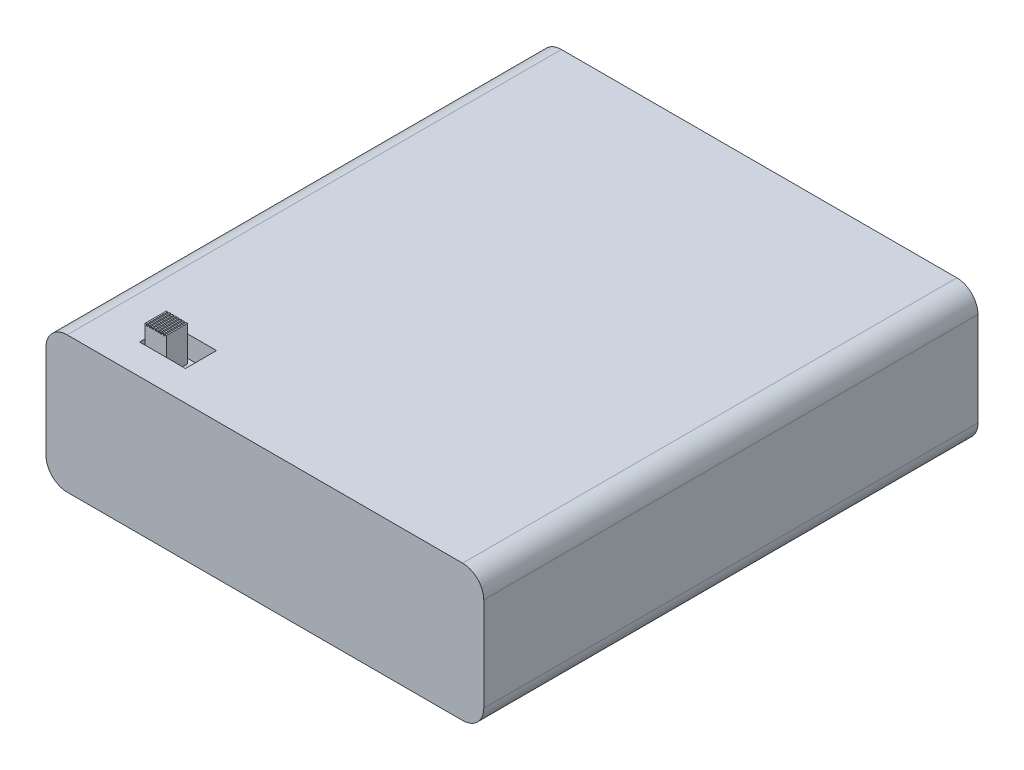
SolidWorks part; units mm, degrees
ref_plane "Front" through (0, 0, 0) normal (0, 0, 1) x (1, 0, 0)
ref_plane "Top" through (0, 0, 0) normal (0, 1, 0) x (1, 0, 0)
ref_plane "Right" through (0, 0, 0) normal (1, 0, 0) x (0, 0, -1)
sketch "Sketch1" plane through (0, 0, 0) normal (0, 0, 1) x (1, 0, 0)
  line L1 (-28, 9.65) -> (28, 9.65)
  line L2 (-31, 6.65) -> (-31, -6.65)
  line L3 (-28, -9.65) -> (28, -9.65)
  line L4 (31, 6.65) -> (31, -6.65)
  line L5 (-31, 9.65) -> (31, -9.65) construction
  line L6 (-31, -9.65) -> (31, 9.65) construction
  arc A0 (28, 9.65) -> (31, 6.65) centre (28, 6.65) cw
  arc A1 (28, -9.65) -> (31, -6.65) centre (28, -6.65) ccw
  arc A2 (-31, -6.65) -> (-28, -9.65) centre (-28, -6.65) ccw
  arc A3 (-28, 9.65) -> (-31, 6.65) centre (-28, 6.65) ccw
  point P0 (0, 0)
  dimension "D3" = 3
  dimension "D1" = 62
  dimension "D2" = 19.3
extrude "Boss-Extrude1" add sketch "Sketch1" along normal mid plane 70
sketch "Sketch2" plane through (0, 9.65, 0) normal (0, 1, 0) x (1, 0, 0)
  line L0 (-31, -35) -> (-31, 35) construction
  line L1 (-22, -26.35) -> (-15.5, -26.35)
  line L2 (-22, -26.35) -> (-22, -30.75)
  line L3 (-22, -30.75) -> (-15.5, -30.75)
  line L4 (-15.5, -26.35) -> (-15.5, -30.75)
  line L5 (28, -35) -> (-28, -35) construction
  dimension "D1" = 6.5
  dimension "D2" = 4.4
  dimension "D3" = 9
  dimension "D4" = 4.25
extrude "Cut-Extrude1" cut sketch "Sketch2" against normal blind 3
sketch "Sketch3" plane through (0, 6.65, 0) normal (0, 1, 0) x (1, 0, 0)
  line L0 (-22, -28.55) -> (-15.5, -28.55) construction
  line L1 (-21.9, -27.05) -> (-18.9, -27.05)
  line L2 (-21.9, -27.05) -> (-21.9, -30.05)
  line L3 (-21.9, -30.05) -> (-18.9, -30.05)
  line L4 (-18.9, -27.05) -> (-18.9, -30.05)
  line L5 (-22, -26.35) -> (-22, -30.75) construction
  line L6 (-15.5, -30.75) -> (-15.5, -26.35) construction
  line L7 (-22, -26.35) -> (-22, -30.75) construction
  point P10 (-21.9, -28.55)
  dimension "D1" = 3
  dimension "D2" = 0.1
extrude "Boss-Extrude2" add sketch "Sketch3" along normal blind 5
sketch "Sketch4" plane through (0, 0, 30.05) normal (0, 0, 1) x (1, 0, 0)
  line L0 (-21.9, 11.65) -> (-18.9, 11.65) construction
  line L1 (-21.7023, 11.65) -> (-21.5023, 11.65)
  line L2 (-21.7023, 11.65) -> (-21.7023, 11.45)
  line L3 (-21.7023, 11.45) -> (-21.5023, 11.45)
  line L4 (-21.5023, 11.65) -> (-21.5023, 11.45)
  line L5 (-21.9, 11.65) -> (-21.9, 6.65) construction
  line L14 (-21.3023, 11.65) -> (-21.3023, 11.45)
  line L15 (-21.3023, 11.65) -> (-21.1023, 11.65)
  line L16 (-21.1023, 11.65) -> (-21.1023, 11.45)
  line L17 (-21.3023, 11.45) -> (-21.1023, 11.45)
  line L18 (-20.9023, 11.65) -> (-20.9023, 11.45)
  line L19 (-20.9023, 11.65) -> (-20.7023, 11.65)
  line L20 (-20.7023, 11.65) -> (-20.7023, 11.45)
  line L21 (-20.9023, 11.45) -> (-20.7023, 11.45)
  line L22 (-20.5023, 11.65) -> (-20.5023, 11.45)
  line L23 (-20.5023, 11.65) -> (-20.3023, 11.65)
  line L24 (-20.3023, 11.65) -> (-20.3023, 11.45)
  line L25 (-20.5023, 11.45) -> (-20.3023, 11.45)
  line L26 (-20.1023, 11.65) -> (-20.1023, 11.45)
  line L27 (-20.1023, 11.65) -> (-19.9023, 11.65)
  line L28 (-19.9023, 11.65) -> (-19.9023, 11.45)
  line L29 (-20.1023, 11.45) -> (-19.9023, 11.45)
  line L30 (-19.7023, 11.65) -> (-19.7023, 11.45)
  line L31 (-19.7023, 11.65) -> (-19.5023, 11.65)
  line L32 (-19.5023, 11.65) -> (-19.5023, 11.45)
  line L33 (-19.7023, 11.45) -> (-19.5023, 11.45)
  line L34 (-19.3023, 11.65) -> (-19.3023, 11.45)
  line L35 (-19.3023, 11.65) -> (-19.1023, 11.65)
  line L36 (-19.1023, 11.65) -> (-19.1023, 11.45)
  line L37 (-19.3023, 11.45) -> (-19.1023, 11.45)
  line L38 (-21.7023, 11.65) -> (-21.3023, 11.65) construction
  dimension "D1" = 0.2
  dimension "D2" = 0.1977
  dimension "D3" = 0.2
  dimension "D5" = 0.4
  dimension "D4" = 7
extrude "Cut-Extrude2" cut sketch "Sketch4" against normal through all
